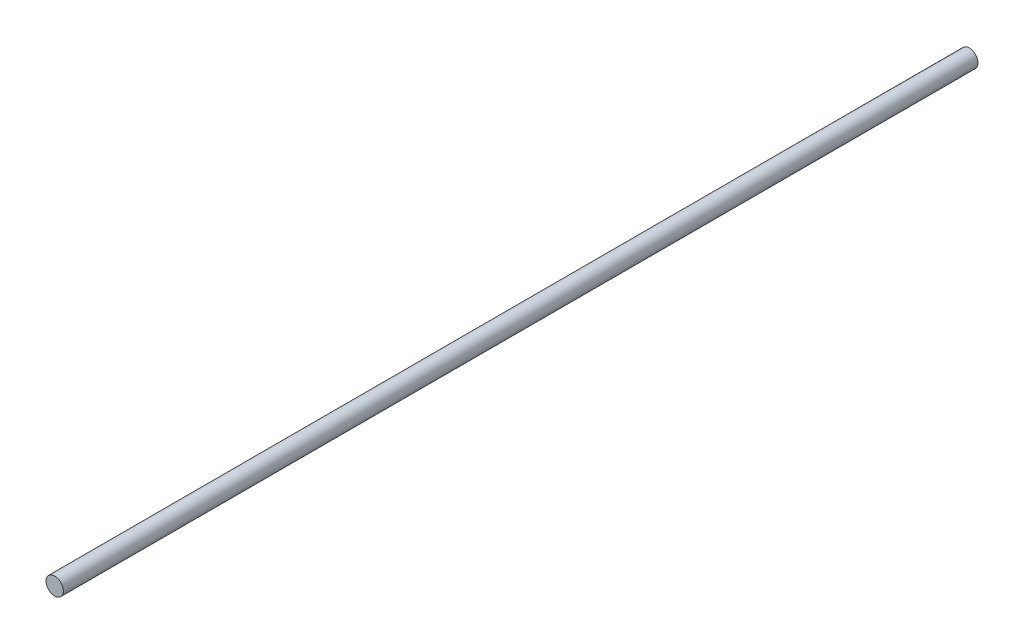
SolidWorks part; units mm, degrees
ref_plane "Front Plane" through (0, 0, 0) normal (0, 0, 1) x (1, 0, 0)
ref_plane "Top Plane" through (0, 0, 0) normal (0, 1, 0) x (1, 0, 0)
ref_plane "Right Plane" through (0, 0, 0) normal (1, 0, 0) x (0, 0, -1)
sketch "Sketch2" plane through (0, 0, 0) normal (0, 0, 1) x (1, 0, 0)
  circle A0 centre (0, 0) radius 4.75
  dimension "D1" = 9.5
extrude "Boss-Extrude1" add sketch "Sketch2" along normal blind 500
